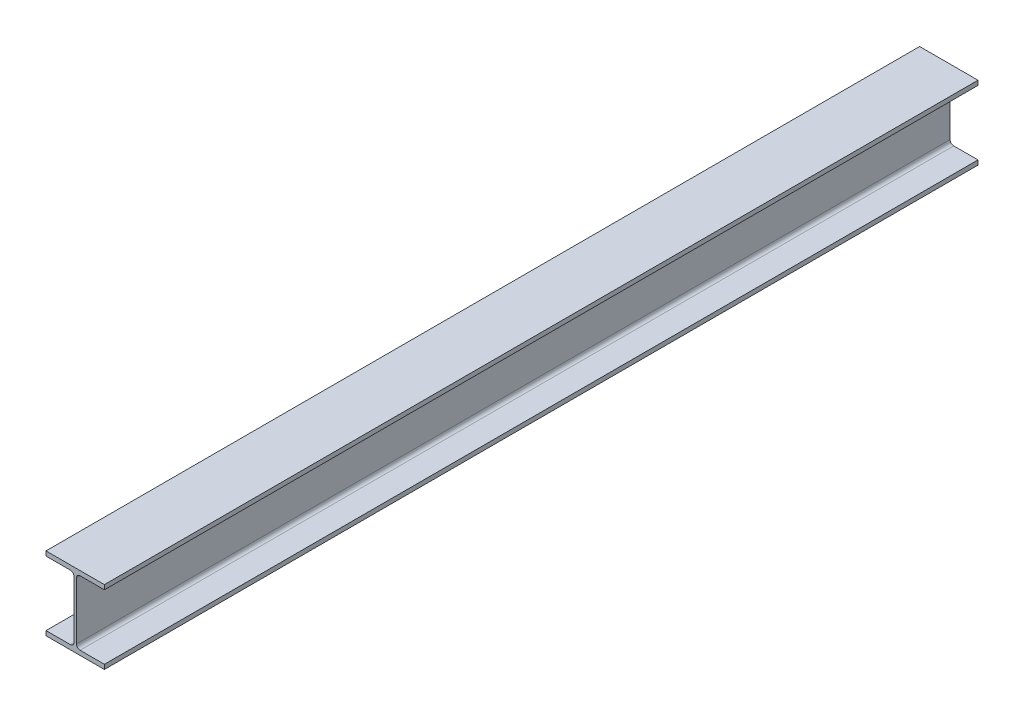
SolidWorks part; units mm, degrees
ref_plane "Plane1" through (0, 0, 0) normal (0, 0, 1) x (1, 0, 0)
ref_plane "Plane2" through (0, 0, 0) normal (0, 1, 0) x (1, 0, 0)
ref_plane "Plane3" through (0, 0, 0) normal (1, 0, 0) x (0, 0, -1)
sketch "Sketch1" plane through (0, 0, 0) normal (0, 0, 1) x (1, 0, 0)
  line L0 (0, 0) -> (0, 15.748)
  line L1 (0, 15.748) -> (84.709, 15.748)
  line L2 (97.409, 28.448) -> (97.409, 228.092)
  line L3 (84.709, 240.792) -> (0, 240.792)
  line L4 (0, 240.792) -> (0, 256.54)
  line L5 (0, 256.54) -> (203.708, 256.54)
  line L6 (203.708, 256.54) -> (203.708, 240.792)
  line L7 (203.708, 240.792) -> (118.999, 240.792)
  line L8 (106.299, 228.092) -> (106.299, 28.448)
  line L9 (118.999, 15.748) -> (203.708, 15.748)
  line L10 (203.708, 15.748) -> (203.708, 0)
  line L11 (203.708, 0) -> (0, 0)
  line L12 (101.854, -72.1361) -> (101.854, 256.54) construction
  arc A0 (84.709, 15.748) -> (97.409, 28.448) centre (84.709, 28.448) ccw
  arc A1 (97.409, 228.092) -> (84.709, 240.792) centre (84.709, 228.092) ccw
  arc A2 (118.999, 240.792) -> (106.299, 228.092) centre (118.999, 228.092) ccw
  arc A3 (106.299, 28.448) -> (118.999, 15.748) centre (118.999, 28.448) ccw
  dimension "Ri" = 12.7
  dimension "Tw" = 8.89
  dimension "Bf" = 203.708
  dimension "Depth" = 256.54
  dimension "Tf" = 15.748
  dimension "D2" = 15.748
  dimension "D1" = 4.445
extrude "BaseSteelW" add sketch "Sketch1" against normal mid plane 3048
sketch "Sketch3" plane through (0, 256.54, 0) normal (0, 1, 0) x (1, 0, 0)
  line L0 (101.854, -1524) -> (101.854, 1524)
  line L1 (203.708, -1524) -> (0, -1524) construction
  line L2 (203.708, 1524) -> (0, 1524) construction
  point P6 (101.854, 0)
equation "\"D1@Sketch1\" = \"Tw@Sketch1\" / 2"
equation "\"D2@Sketch1\" = \"Tf@Sketch1\""
